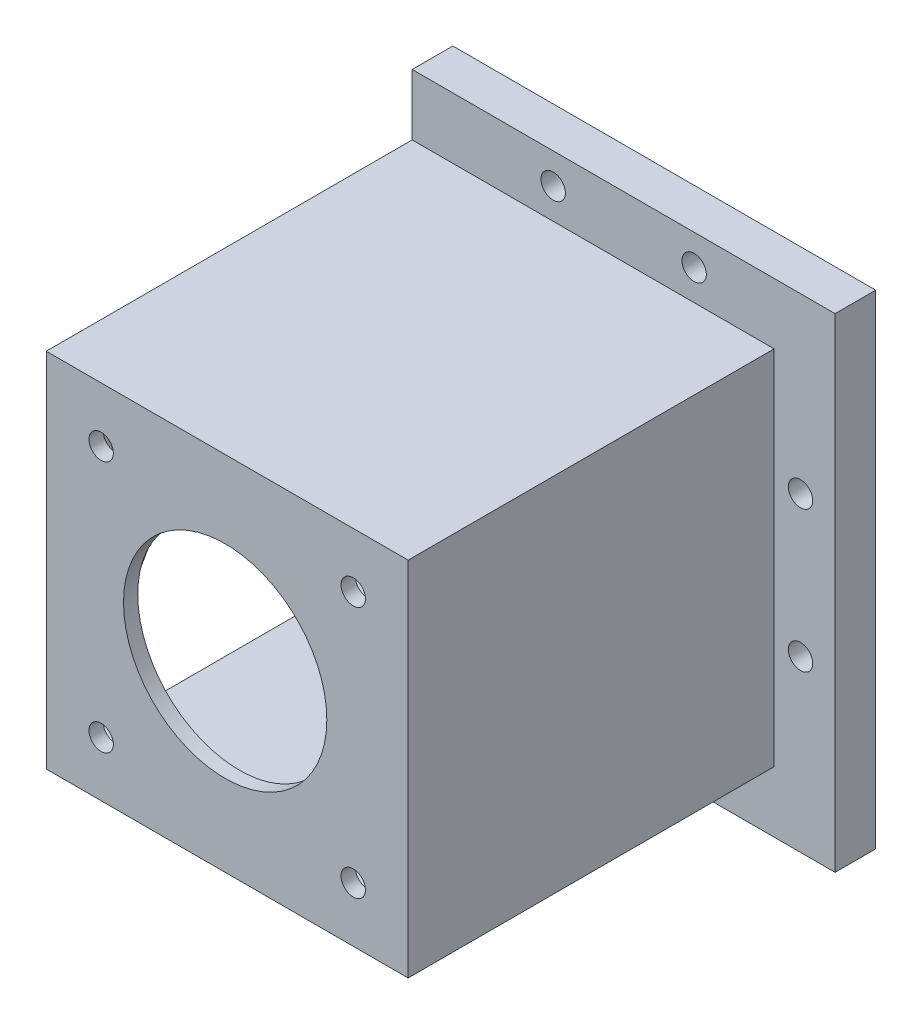
SolidWorks part; units mm, degrees
ref_plane "Front Plane" through (0, 0, 0) normal (0, 0, 1) x (1, 0, 0)
ref_plane "Top Plane" through (0, 0, 0) normal (0, 1, 0) x (1, 0, 0)
ref_plane "Right Plane" through (0, 0, 0) normal (1, 0, 0) x (0, 0, -1)
sketch "Sketch6" plane through (0, 0, 0) normal (0, 0, 1) x (1, 0, 0)
  line L1 (-482.0212, -225.0811) -> (-437.5212, -225.0811)
  line L2 (-482.0212, -225.0811) -> (-482.0212, -180.5811)
  line L3 (-482.0212, -180.5811) -> (-437.5212, -180.5811)
  line L4 (-437.5212, -225.0811) -> (-437.5212, -180.5811)
  line L8 (-430.0212, -232.5811) -> (-430.0212, -173.0811)
  line L9 (-482.0212, -173.0811) -> (-430.0212, -173.0811)
  line L10 (-482.0212, -173.0811) -> (-482.0212, -232.5811)
  line L11 (-482.0212, -232.5811) -> (-430.0212, -232.5811)
  line L12 (-430.0212, -173.0811) -> (-430.0212, -232.5811)
  circle A0 centre (-460.0212, -202.5811) radius 12.5
  circle A1 centre (-475.2712, -187.3311) radius 1.5
  circle A2 centre (-444.2712, -187.3311) radius 1.5
  circle A3 centre (-444.2712, -218.3311) radius 1.5
  circle A4 centre (-475.2712, -218.3311) radius 1.5
  circle A8 centre (-464.6879, -228.3311) radius 1.5
  circle A9 centre (-447.3545, -228.3311) radius 1.5
  circle A12 centre (-447.3546, -176.8311) radius 1.5
  circle A13 centre (-464.6879, -176.8311) radius 1.5
  circle A14 centre (-434.2712, -211.7157) radius 1.5
  circle A15 centre (-434.2712, -194.3823) radius 1.5
  point P29 (-460.0212, -202.5811)
  point P38 (-456.0212, -202.5811)
  dimension "D9" = 25
  dimension "D10" = 3
  dimension "D7" = 22
  dimension "D15" = 17.3333
  dimension "D3" = 3
  dimension "D1" = 44.5
  dimension "D2" = 44.5
  dimension "D4" = 7.5
  dimension "D5" = 17.3333
  dimension "D6" = 17.3333
  dimension "D8" = 22
  dimension "D11" = 6.75
  dimension "D14" = 6.75
  dimension "D16" = 17.3333
  dimension "D17" = 3.25
  dimension "D19" = 52
  dimension "D20" = 3.25
  dimension "D18" = 3.25
  dimension "D12" = 2
  dimension "D13" = 2
sketch "Sketch7" plane through (0, 0, 0) normal (0, 0, 1) x (1, 0, 0)
  line L0 (-437.5212, -225.0811) -> (-437.5212, -180.5811) construction
  line L1 (-482.0212, -224.0811) -> (-438.5212, -224.0811)
  line L2 (-482.0212, -224.0811) -> (-482.0212, -181.5811)
  line L3 (-482.0212, -181.5811) -> (-438.5212, -181.5811)
  line L4 (-438.5212, -224.0811) -> (-438.5212, -181.5811)
  line L5 (-482.0212, -180.5811) -> (-437.5212, -180.5811) construction
  dimension "D3" = 43.5
  dimension "D4" = 42.5
  dimension "D5" = 1
  dimension "D6" = 1
sketch "Sketch8" plane through (0, 0, 0) normal (0, 0, 1) x (1, 0, 0)
  line L1 (-482.0212, -225.0811) -> (-437.5212, -225.0811)
  line L2 (-482.0212, -225.0811) -> (-482.0212, -180.5811)
  line L3 (-482.0212, -180.5811) -> (-437.5212, -180.5811)
  line L4 (-437.5212, -225.0811) -> (-437.5212, -180.5811)
  line L5 (-489.5212, -232.5811) -> (-430.0212, -232.5811)
  line L6 (-489.5212, -232.5811) -> (-489.5212, -173.0811)
  line L7 (-489.5212, -173.0811) -> (-430.0212, -173.0811)
  line L8 (-430.0212, -232.5811) -> (-430.0212, -173.0811)
  circle A0 centre (-460.0212, -202.5811) radius 12.5
  circle A1 centre (-475.2712, -187.3311) radius 1.5
  circle A2 centre (-444.2712, -187.3311) radius 1.5
  circle A3 centre (-444.2712, -218.3311) radius 1.5
  circle A4 centre (-475.2712, -218.3311) radius 1.5
  dimension "D9" = 25
  dimension "D10" = 3
  dimension "D7" = 22
  dimension "D1" = 44.5
  dimension "D2" = 44.5
  dimension "D3" = 7.5
  dimension "D4" = 7.5
  dimension "D5" = 7.5
  dimension "D6" = 7.5
  dimension "D8" = 22
  dimension "D11" = 6.75
  dimension "D14" = 6.75
  dimension "D12" = 2
  dimension "D13" = 2
extrude "Boss-Extrude4" add sketch "Sketch6" along normal blind 5
extrude "Boss-Extrude5" add sketch "Sketch8" along normal blind 50 contours L1 L4 L3 L2 A4 A3 A2 A1 A0
extrude "Cut-Extrude4" cut sketch "Sketch7" along normal blind 48.25
sketch "Sketch10" plane through (-482.0212, 0, 0) normal (-1, 0, 0) x (0, 0, 1)
  line L0 (24.125, -181.5811) -> (48.25, -224.0811)
  line L1 (48.25, -181.5811) -> (0, -181.5811) construction
  line L2 (48.25, -224.0811) -> (48.25, -181.5811)
  line L3 (48.25, -181.5811) -> (24.125, -181.5811)
extrude "Boss-Extrude6" add sketch "Sketch10" against normal blind 1
sketch "Sketch13" plane through (0, 0, 0) normal (0, 0, 1) x (1, 0, 0)
  point P0 (-460.0212, -202.5811)
sketch "Sketch17" plane through (0, 0, 0) normal (0, 0, 1) x (1, 0, 0)
  line L1 (-482.0212, -225.0811) -> (-437.5212, -225.0811)
  line L2 (-482.0212, -225.0811) -> (-482.0212, -180.5811)
  line L3 (-482.0212, -180.5811) -> (-437.5212, -180.5811)
  line L4 (-437.5212, -225.0811) -> (-437.5212, -180.5811)
  line L5 (-489.5212, -232.5811) -> (-430.0212, -232.5811)
  line L6 (-489.5212, -232.5811) -> (-489.5212, -173.0811)
  line L7 (-489.5212, -173.0811) -> (-430.0212, -173.0811)
  line L8 (-430.0212, -232.5811) -> (-430.0212, -173.0811)
  circle A0 centre (-460.0212, -202.5811) radius 12.5
  circle A1 centre (-475.2712, -187.3311) radius 1.5
  circle A2 centre (-444.2712, -187.3311) radius 1.5
  circle A3 centre (-444.2712, -218.3311) radius 1.5
  circle A4 centre (-475.2712, -218.3311) radius 1.5
  dimension "D9" = 25
  dimension "D10" = 3
  dimension "D7" = 22
  dimension "D1" = 44.5
  dimension "D2" = 44.5
  dimension "D3" = 7.5
  dimension "D4" = 7.5
  dimension "D5" = 7.5
  dimension "D6" = 7.5
  dimension "D8" = 22
  dimension "D11" = 6.75
  dimension "D14" = 6.75
  dimension "D12" = 2
  dimension "D13" = 2
